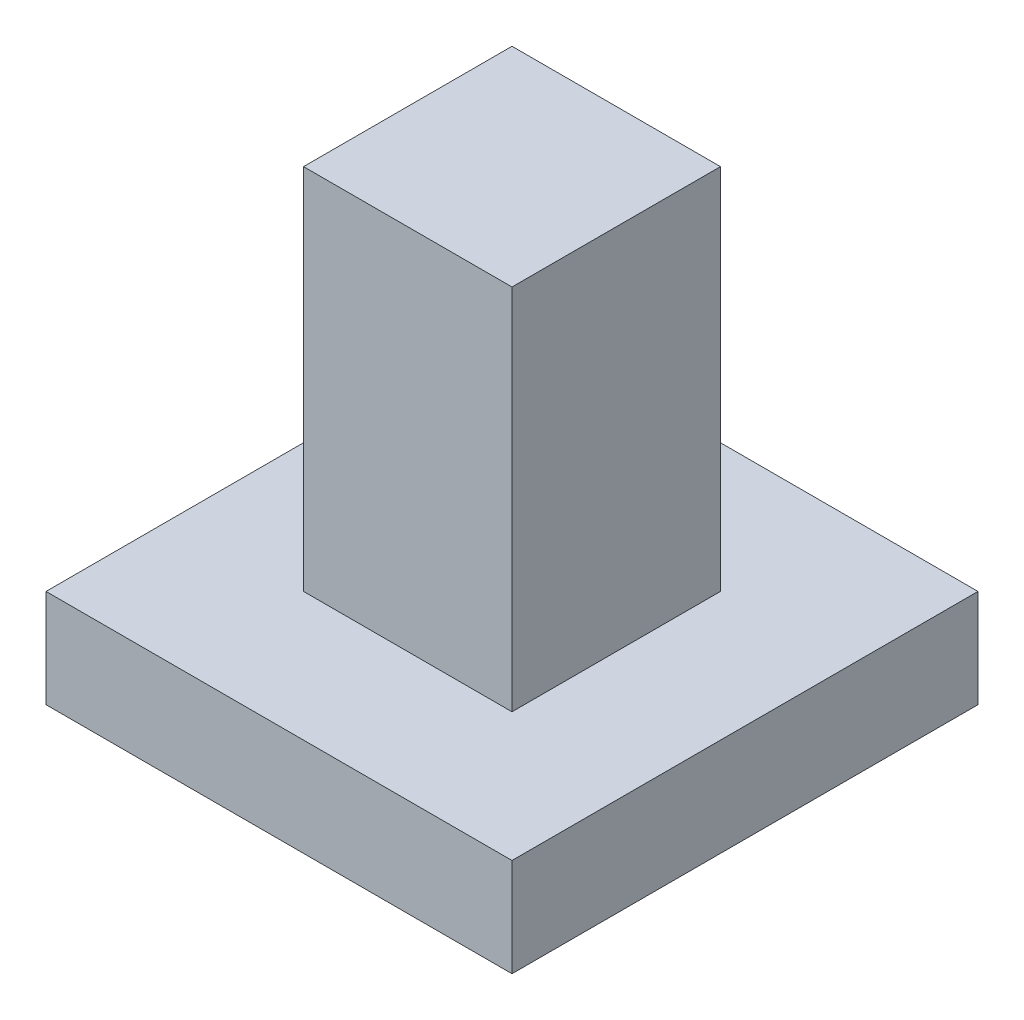
SolidWorks part; units mm, degrees
ref_plane "前视基准面" through (0, 0, 0) normal (0, 0, 1) x (1, 0, 0)
ref_plane "上视基准面" through (0, 0, 0) normal (0, 1, 0) x (1, 0, 0)
ref_plane "右视基准面" through (0, 0, 0) normal (1, 0, 0) x (0, 0, -1)
sketch "草图1" plane through (0, 0, 0) normal (0, 1, 0) x (1, 0, 0)
  line L1 (-7.6, 7.6) -> (0, 7.6)
  line L2 (-7.6, 7.6) -> (-7.6, 0)
  line L3 (-7.6, 0) -> (0, 0)
  line L4 (0, 7.6) -> (0, 0)
extrude "凸台-拉伸1" add sketch "草图1" along normal blind 1.6
sketch "草图2" plane through (0, 1.6, 0) normal (0, 1, 0) x (1, 0, 0)
  line L1 (-2.1, 2.1) -> (-5.5, 2.1)
  line L2 (-2.1, 2.1) -> (-2.1, 5.5)
  line L3 (-2.1, 5.5) -> (-5.5, 5.5)
  line L4 (-5.5, 2.1) -> (-5.5, 5.5)
extrude "凸台-拉伸2" add sketch "草图2" along normal blind 6
